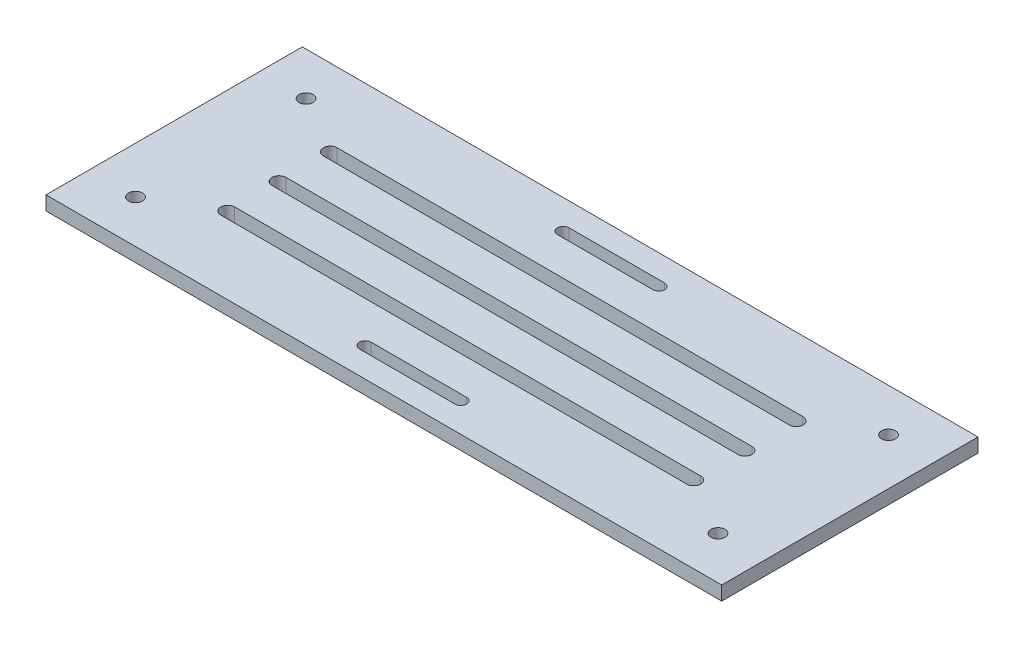
SolidWorks part; units mm, degrees
ref_plane "Plano frontal" through (0, 0, 0) normal (0, 0, 1) x (1, 0, 0)
ref_plane "Plano superior" through (0, 0, 0) normal (0, 1, 0) x (1, 0, 0)
ref_plane "Plano direito" through (0, 0, 0) normal (1, 0, 0) x (0, 0, -1)
sketch "Esboço1" plane through (0, 0, 0) normal (0, 1, 0) x (1, 0, 0)
  line L1 (-72.5, -27.5) -> (72.5, -27.5)
  line L2 (-72.5, -27.5) -> (-72.5, 27.5)
  line L3 (-72.5, 27.5) -> (72.5, 27.5)
  line L4 (72.5, -27.5) -> (72.5, 27.5)
  line L5 (-72.5, -27.5) -> (72.5, 27.5) construction
  line L6 (-72.5, 27.5) -> (72.5, -27.5) construction
  point P0 (0, 0)
  dimension "D1" = 145
  dimension "D2" = 55
extrude "Ressalto-extrusão1" add sketch "Esboço1" along normal blind 3
sketch "Esboço2" plane through (0, 3, 0) normal (0, 1, 0) x (1, 0, 0)
  line L0 (0, 0) -> (-72.5, 0) construction
  line L1 (-72.5, 27.5) -> (-72.5, -27.5) construction
  line L2 (0, 0) -> (0, 27.5) construction
  line L3 (72.5, 27.5) -> (-72.5, 27.5) construction
  line L4 (-10.25, 21.25) -> (10.25, 21.25) construction
  line L5 (-10.25, 22.5) -> (10.25, 22.5)
  line L6 (-10.25, 20) -> (10.25, 20)
  line L7 (-50, 11) -> (50, 11) construction
  line L8 (-50, 12.5) -> (50, 12.5)
  line L9 (-50, 9.5) -> (50, 9.5)
  line L10 (-10.25, -21.25) -> (10.25, -21.25) construction
  line L11 (-10.25, -22.5) -> (10.25, -22.5)
  line L12 (-10.25, -20) -> (10.25, -20)
  line L13 (-50, -11) -> (50, -11) construction
  line L14 (-50, -12.5) -> (50, -12.5)
  line L15 (-50, -9.5) -> (50, -9.5)
  line L16 (-50, 0) -> (50, 0) construction
  line L17 (-50, 1.5) -> (50, 1.5)
  line L18 (-50, -1.5) -> (50, -1.5)
  circle A0 centre (-62.5, 18.3) radius 1.5
  circle A1 centre (-62.5, -18.3) radius 1.5
  arc A4 (-10.25, 22.5) -> (-10.25, 20) centre (-10.25, 21.25) ccw
  arc A5 (10.25, 20) -> (10.25, 22.5) centre (10.25, 21.25) ccw
  arc A6 (-50, 12.5) -> (-50, 9.5) centre (-50, 11) ccw
  arc A7 (50, 9.5) -> (50, 12.5) centre (50, 11) ccw
  circle A8 centre (62.5, -18.3) radius 1.5
  circle A9 centre (62.5, 18.3) radius 1.5
  arc A10 (-10.25, -22.5) -> (-10.25, -20) centre (-10.25, -21.25) cw
  arc A11 (10.25, -20) -> (10.25, -22.5) centre (10.25, -21.25) cw
  arc A12 (-50, -12.5) -> (-50, -9.5) centre (-50, -11) cw
  arc A13 (50, -9.5) -> (50, -12.5) centre (50, -11) cw
  arc A14 (-50, 1.5) -> (-50, -1.5) centre (-50, 0) ccw
  arc A15 (50, -1.5) -> (50, 1.5) centre (50, 0) ccw
  point P6 (0, 11)
  point P18 (0, 21.25)
  point P30 (0, 0)
  point P33 (0, -21.25)
  point P40 (0, -11)
  point P51 (0, 0)
  point P52 (0, 0)
  point P53 (0, 0)
  dimension "D1" = 3
  dimension "D6" = 20.5
  dimension "D2" = 9.2
  dimension "D3" = 10
  dimension "D4" = 5
  dimension "D5" = 2.5
  dimension "D7" = 3
  dimension "D8" = 100
  dimension "D9" = 15
  dimension "D10" = 3
  dimension "D11" = 100
extrude "Corte-extrusão1" cut sketch "Esboço2" against normal blind 3
